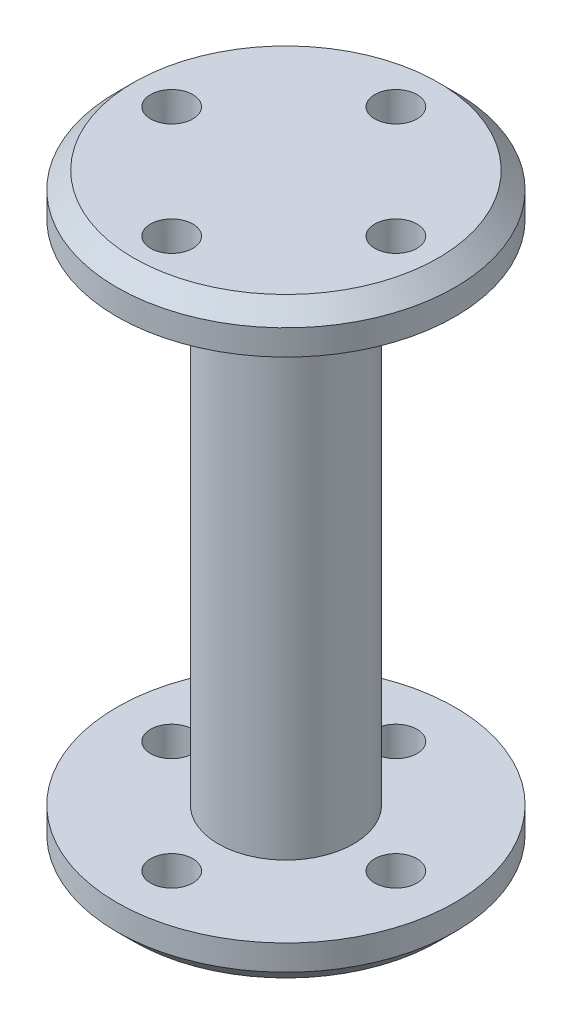
SolidWorks part; units mm, degrees
ref_plane "Front Plane" through (0, 0, 0) normal (0, 0, 1) x (1, 0, 0)
ref_plane "Top Plane" through (0, 0, 0) normal (0, 1, 0) x (1, 0, 0)
ref_plane "Right Plane" through (0, 0, 0) normal (1, 0, 0) x (0, 0, -1)
sketch "Sketch1" plane through (0, 0, 0) normal (0, 1, 0) x (1, 0, 0)
  circle A0 centre (0, 0) radius 8
  dimension "ShaftDiameter" = 16
extrude "Boss-Extrude1" add sketch "Sketch1" along normal mid plane 60
sketch "Sketch2" plane through (0, 30, 0) normal (0, 1, 0) x (1, 0, 0)
  circle A0 centre (0, 0) radius 20
  dimension "CapDiameter" = 40
extrude "Boss-Extrude2" add sketch "Sketch2" along normal blind 5
chamfer "Chamfer1" distance 2 angle 45 1 edges at (0, 35, 20)
sketch "Sketch3" plane through (0, 35, 0) normal (0, 1, 0) x (1, 0, 0)
  line L0 (0, 18) -> (0, 8) construction
  circle A0 centre (0, 0) radius 18 construction
  circle A1 centre (0, 0) radius 8 construction
  circle A2 centre (0, 13) radius 2.5
  dimension "D1" = 5
extrude "Cut-Extrude1" cut sketch "Sketch3" against normal through all
pattern_circular "CirPattern1" count 4 over 360 about axis through (0, 0, 0.2557) along (0, 1, 0) of "Cut-Extrude1"
hole_wizard "CBORE for #12 Binding Head Machine Screw1" positions "Sketch4" profile "Sketch5" counterbore size "#12" standard "ANSI Inch"
sketch "Sketch4" plane through (0, 145, 0) normal (0, 1, 0) x (1, 0, 0)
  point P0 (0, 0)
sketch "Sketch5" plane through (0, 145, 0) normal (1, 0, 0) x (0, 0, 1)
  line L0 (0, 0) -> (0, 285)
  line L1 (0, 285) -> (2.8956, 285)
  line L3 (2.8956, 285) -> (2.8956, 3.5814)
  line L4 (2.8956, 3.5814) -> (20, 3.5814)
  line L5 (20, 3.5814) -> (20, 0)
  line L7 (20, 0) -> (0, 0)
  line L11 (0, -6.35) -> (0, 107.95) construction
  dimension "Thru Hole Dia." = 5.7912
  dimension "Thru Hole Depth" = 285
  dimension "C'Bore Dia." = 39.9999
  dimension "C'Bore Depth" = 3.5814
hole_wizard "CBORE for #12 Binding Head Machine Screw3" positions "Sketch8" profile "Sketch9" counterbore size "#12" standard "ANSI Inch"
sketch "Sketch8" plane through (0, 55, 0) normal (0, 1, 0) x (1, 0, 0)
  point P0 (0, 0)
sketch "Sketch9" plane through (0, 55, 0) normal (1, 0, 0) x (0, 0, 1)
  line L0 (0, 0) -> (0, 105)
  line L1 (0, 105) -> (2.8956, 105)
  line L3 (2.8956, 105) -> (2.8956, 3.5814)
  line L4 (2.8956, 3.5814) -> (20, 3.5814)
  line L5 (20, 3.5814) -> (20, 0)
  line L7 (20, 0) -> (0, 0)
  line L11 (0, -6.35) -> (0, 107.95) construction
  dimension "Thru Hole Dia." = 5.7912
  dimension "Thru Hole Depth" = 105
  dimension "C'Bore Dia." = 39.9999
  dimension "C'Bore Depth" = 3.5814
mirror "Mirror1" about plane through (0, 0, 0) normal (0, 1, 0) of bodies 104 106
equation "\"NumHoles\"=6"
